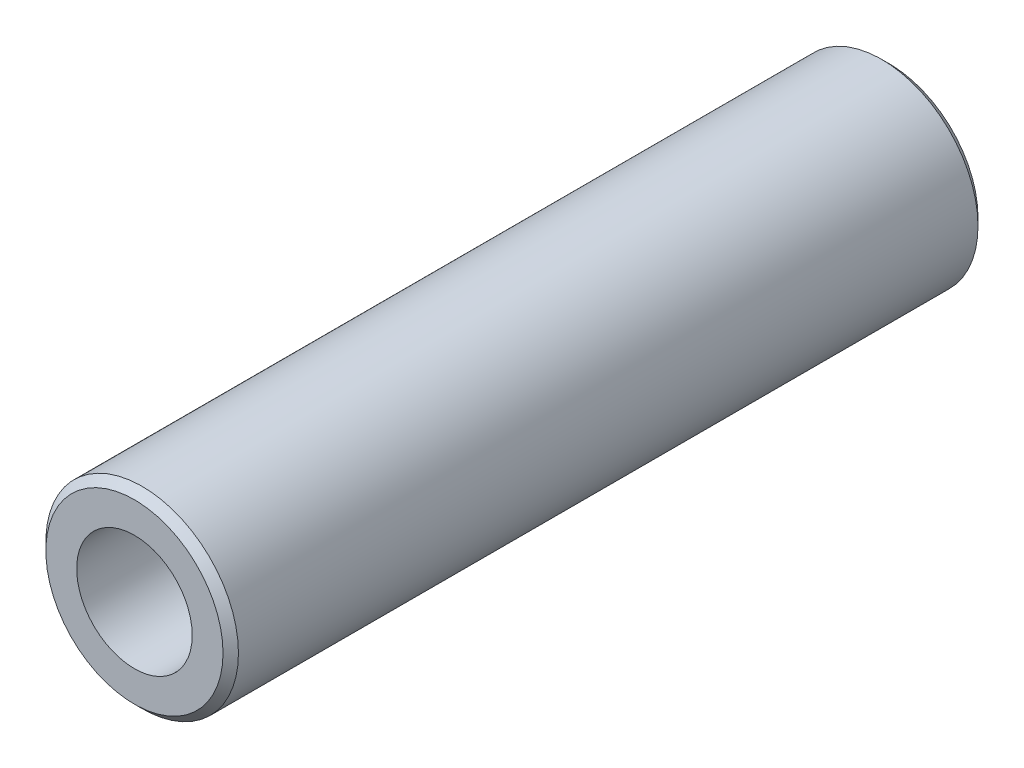
SolidWorks part; units mm, degrees
ref_plane "Front Plane" through (0, 0, 0) normal (0, 0, 1) x (1, 0, 0)
ref_plane "Top Plane" through (0, 0, 0) normal (0, 1, 0) x (1, 0, 0)
ref_plane "Right Plane" through (0, 0, 0) normal (1, 0, 0) x (0, 0, -1)
sketch "Sketch1" plane through (0, 0, 0) normal (0, 0, 1) x (1, 0, 0)
  circle A0 centre (0, 0) radius 6.25
  dimension "D1" = 12.5
extrude "Extrude-Thin1" add sketch "Sketch1" along normal mid plane 49 thin thin type one direction reverse wall 2.5
chamfer "Chamfer1" distance 0.5 angle 45 2 edges at (6.25, 0, 24.5) (6.25, 0, -24.5)
